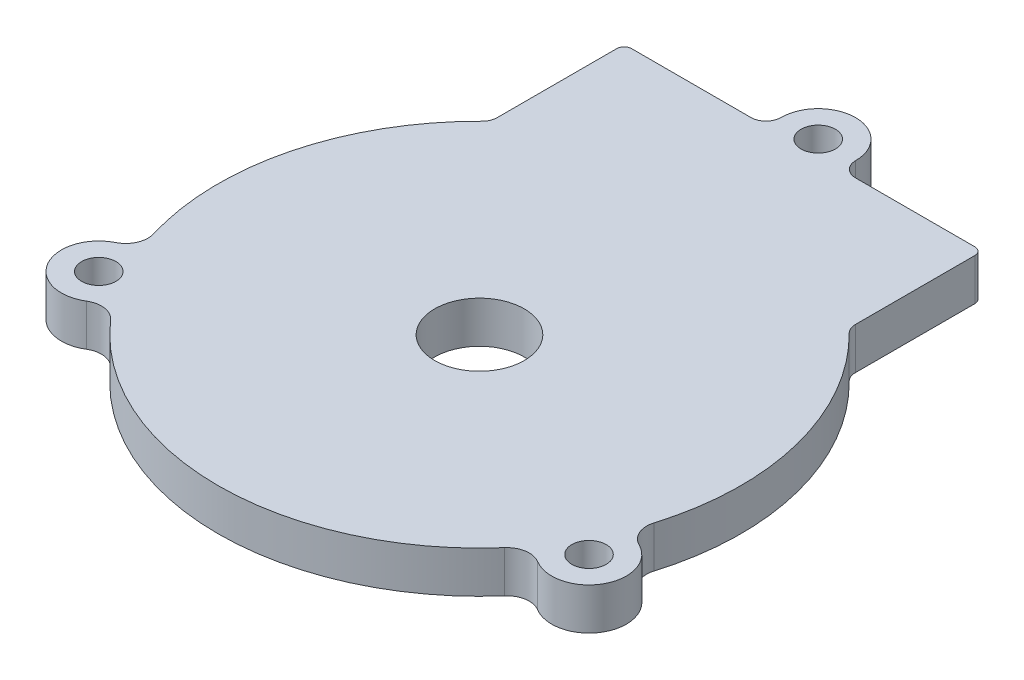
SolidWorks part; units mm, degrees
ref_plane "Front Plane" through (0, 0, 0) normal (0, 0, 1) x (1, 0, 0)
ref_plane "Top Plane" through (0, 0, 0) normal (0, 1, 0) x (1, 0, 0)
ref_plane "Right Plane" through (0, 0, 0) normal (1, 0, 0) x (0, 0, -1)
sketch "Sketch1" plane through (0, 0, 0) normal (0, 1, 0) x (1, 0, 0)
  line L2 (32.785, 0) -> (32.785, 24.2952) construction
  line L7 (32.785, 0) -> (32.785, 18.8) construction
  line L10 (32.785, 66.7015) -> (56.765, 66.7015) construction
  line L11 (32.785, 66.7015) -> (32.785, 59.7015) construction
  line L12 (32.785, 59.7015) -> (56.765, 59.7015) construction
  line L13 (56.765, 66.7015) -> (56.765, 59.7015) construction
  line L15 (56.765, 66.7015) -> (8.805, 66.7015)
  line L16 (56.765, 66.7015) -> (56.765, 41.7015)
  line L17 (56.765, 41.7015) -> (8.805, 41.7015)
  line L18 (8.805, 66.7015) -> (8.805, 41.7015)
  circle A0 centre (32.785, 23.3515) radius 35
  circle A1 centre (65.6, 5.2015) radius 5
  circle A4 centre (-0.03, 5.2015) radius 5
  circle A6 centre (-0.03, 5.2015) radius 2.3
  circle A7 centre (65.6, 5.2015) radius 2.3
  circle A8 centre (32.785, 23.3515) radius 6
  circle A9 centre (32.785, 68.7015) radius 2.3
  circle A10 centre (32.785, 68.7015) radius 5
  point P7 (32.785, 0)
  dimension "D1" = 7
  dimension "D5" = 43.35
  dimension "D7" = 37.5
  dimension "D10" = 4.6
  dimension "D11" = 2
  dimension "D13" = 10
  dimension "D2" = 23.98
  dimension "D3" = 47.96
  dimension "D4" = 25
  dimension "D6" = 37.5
  dimension "D8" = 61.5
  dimension "D9" = 61.5
  dimension "D12" = 0
extrude "Boss-Extrude3" add sketch "Sketch1" along normal blind 5.588 contours A4 | A1 | A0 | L15 L18 L17 L16 | A10 | A6 | A7 | A8
hole_wizard "Ø4.6 (4.6) Diameter Hole1" positions "Sketch4" profile "Sketch5" hole size "Ø4.6" standard "ANSI Metric" end condition through all
sketch "Sketch4" plane through (0, 5.588, 0) normal (0, 1, 0) x (1, 0, 0)
  point P0 (32.785, 68.7015)
sketch "Sketch5" plane through (32.785, 5.588, -68.7015) normal (1, 0, 0) x (0, 0, 1)
  line L0 (0, 0) -> (0, 5.588)
  line L1 (0, 5.588) -> (2.3, 5.588)
  line L2 (2.3, 5.588) -> (2.3, 0)
  line L5 (2.3, 0) -> (0, 0)
  line L11 (0, -6.35) -> (0, 107.95) construction
  dimension "Thru Hole Dia." = 4.6
  dimension "Thru Hole Depth" = 5.588
fillet "Fillet1" radius 3 4 edges at (65.2147, 2.794, -10.1866) (61.1725, 2.794, -2.8783) (4.3975, 2.794, -2.8783) (0.3553, 2.794, -10.1866)
fillet "Fillet2" radius 2 2 edges at (28.2024, 2.794, -66.7015) (37.3676, 2.794, -66.7015)
fillet "Fillet3" radius 2 2 edges at (56.765, 2.794, -48.8458) (8.805, 2.794, -48.8458)
fillet "Fillet4" radius 1 2 edges at (8.805, 2.794, -66.7015) (56.765, 2.794, -66.7015)
